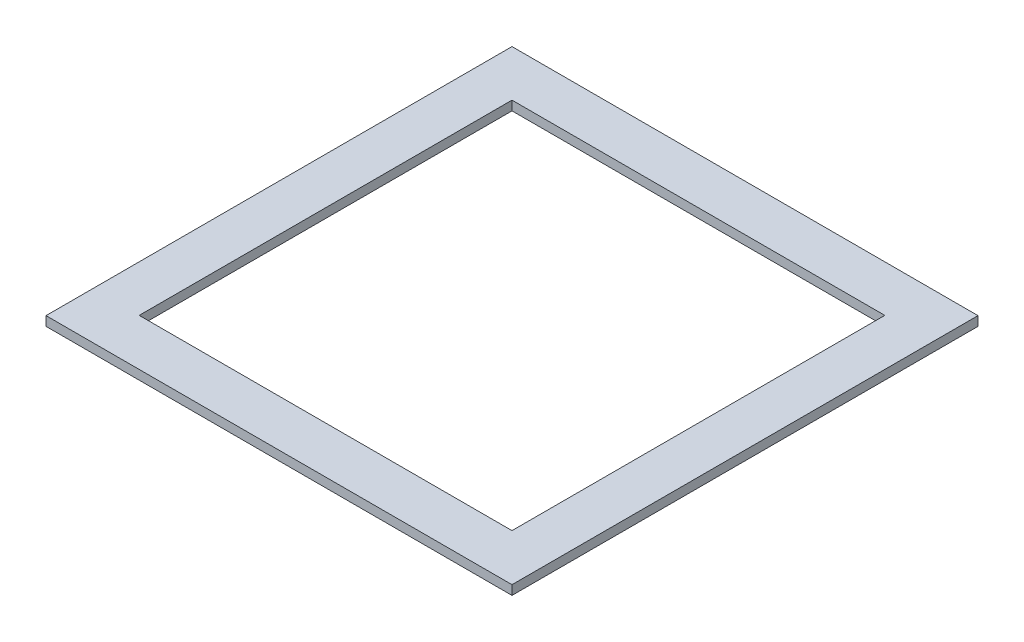
SolidWorks part; units mm, degrees
ref_plane "Front Plane" through (0, 0, 0) normal (0, 0, 1) x (1, 0, 0)
ref_plane "Top Plane" through (0, 0, 0) normal (0, 1, 0) x (1, 0, 0)
ref_plane "Right Plane" through (0, 0, 0) normal (1, 0, 0) x (0, 0, -1)
sketch "Sketch1" plane through (0, 0, 0) normal (0, 1, 0) x (1, 0, 0)
  line L0 (0, 100) -> (100, 0) construction
  line L1 (0, 0) -> (100, 0)
  line L2 (0, 0) -> (0, 100)
  line L3 (0, 100) -> (100, 100)
  line L4 (100, 0) -> (100, 100)
  line L8 (148.2257, 61.5592) -> (158.2257, 61.5592) construction
  line L9 (0, 100) -> (0, 90.0469)
  line L10 (0, 90.0469) -> (9.9531, 90.0469) construction
  line L11 (9.9531, 90.0469) -> (9.9531, 10.0469)
  line L12 (9.9531, 10.0469) -> (89.9531, 10.0469)
  line L13 (89.9531, 10.0469) -> (89.9531, 90.0469)
  line L14 (89.9531, 90.0469) -> (9.9531, 90.0469)
  point P14 (0, 0)
extrude "Boss-Extrude1" add sketch "Sketch1" along normal blind 2 contours L1 L4 L3 L2 L14 L13 L12 L11
